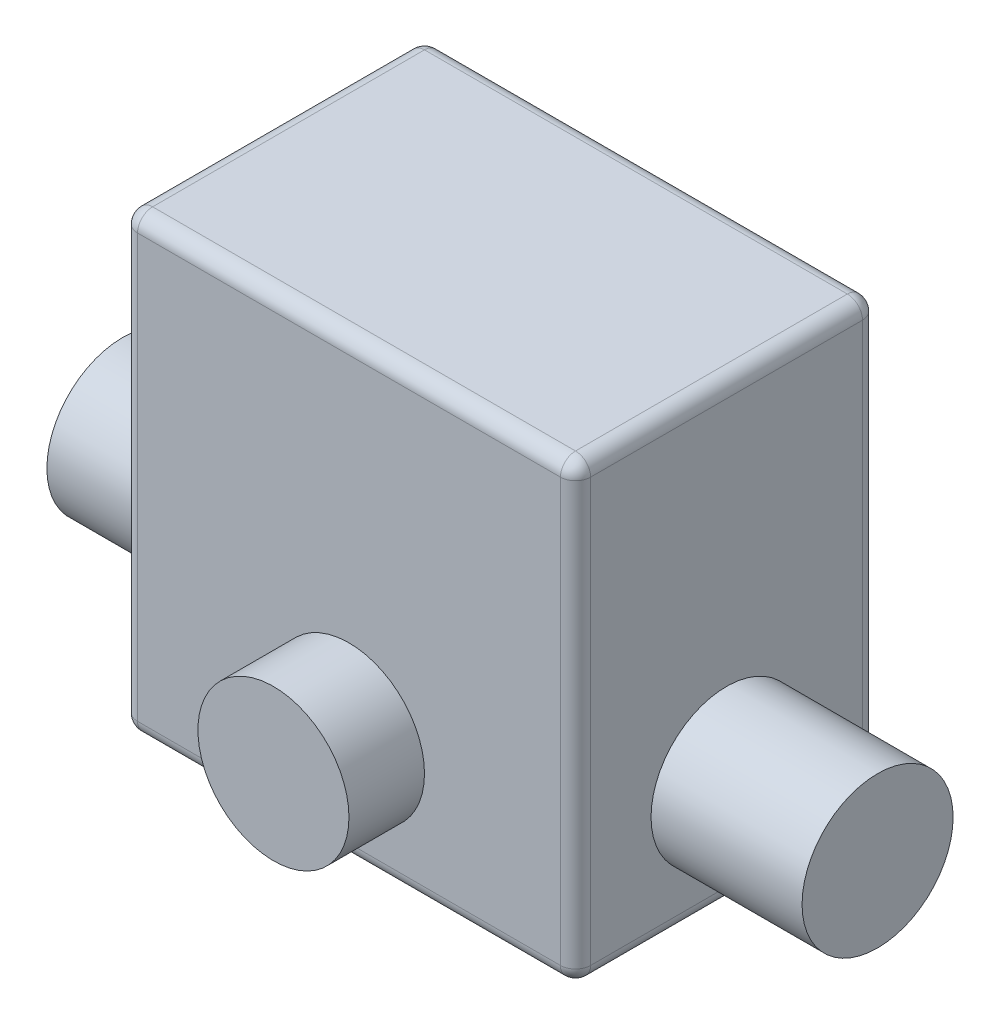
SolidWorks part; units mm, degrees
ref_plane "Front Plane" through (0, 0, 0) normal (0, 0, 1) x (1, 0, 0)
ref_plane "Top Plane" through (0, 0, 0) normal (0, 1, 0) x (1, 0, 0)
ref_plane "Right Plane" through (0, 0, 0) normal (1, 0, 0) x (0, 0, -1)
sketch "Sketch1" plane through (0, 0, 0) normal (0, 0, 1) x (1, 0, 0)
  line L1 (0, 0) -> (3, 0)
  line L2 (0, 0) -> (0, 3)
  line L3 (0, 3) -> (3, 3)
  line L4 (3, 0) -> (3, 3)
  dimension "D1" = 3
  dimension "D2" = 3
extrude "Boss-Extrude1" add sketch "Sketch1" along normal blind 2 contours L2 L3 L4 L1
ref_plane "Plane1" through (1.5, 0, 0) normal (1, 0, 0) x (0, 0, -1)
sketch "Sketch3" plane through (1.5, 0, 0) normal (1, 0, 0) x (0, 0, -1)
  line L0 (-1, 0) -> (-1, 0.75) construction
  line L1 (-2, 0) -> (0, 0) construction
  circle A0 centre (-1, 0.75) radius 0.5
  dimension "D2" = 1
  dimension "D1" = 0.75
extrude "Boss-Extrude2" add sketch "Sketch3" along normal mid plane 5
fillet "Fillet1" radius 0.1 12 edges at (3, 3, 1) (3, 1.5, 2) (0, 1.5, 2) (1.5, 3, 2) (3, 1.5, 0) (1.5, 3, 0) (0, 3, 1) (0, 1.5, 0) (1.5, 0, 2) (0, 0, 1) (1.5, 0, 0) (3, 0, 1)
sketch "Sketch4" plane through (0, 0, 2) normal (0, 0, 1) x (1, 0, 0)
  line L0 (1.5, 0) -> (1.5, 0.75) construction
  line L1 (2.9, 0) -> (0.1, 0) construction
  line L2 (1.5, -1.1) -> (1.5, 1.1) construction
  circle A0 centre (1.5, 0.75) radius 0.5
  dimension "D2" = 1
  dimension "D1" = 0.75
extrude "Boss-Extrude3" add sketch "Sketch4" along normal blind 0.5
